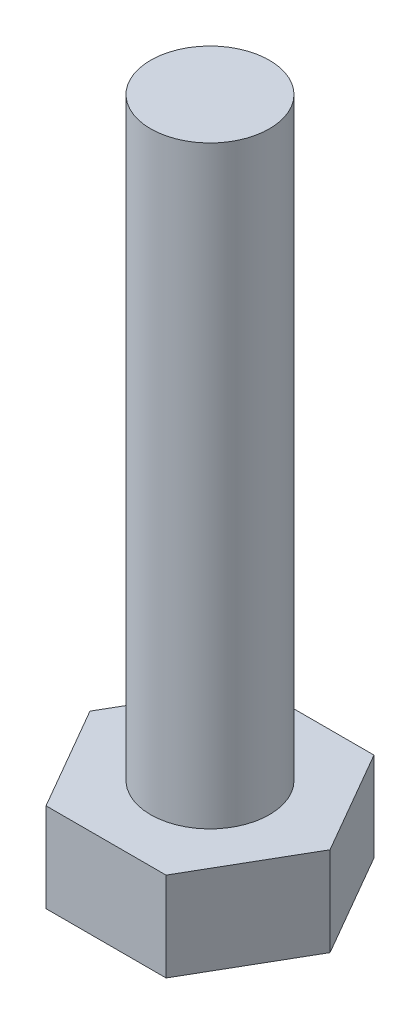
SolidWorks part; units mm, degrees
ref_plane "Front Plane" through (0, 0, 0) normal (0, 0, 1) x (1, 0, 0)
ref_plane "Top Plane" through (0, 0, 0) normal (0, 1, 0) x (1, 0, 0)
ref_plane "Right Plane" through (0, 0, 0) normal (1, 0, 0) x (0, 0, -1)
sketch "Sketch1" plane through (0, 0, 0) normal (0, 1, 0) x (1, 0, 0)
  line L1 (-4.0415, 0) -> (-2.0207, -3.5)
  line L2 (-2.0207, -3.5) -> (2.0207, -3.5)
  line L3 (2.0207, -3.5) -> (4.0415, 0)
  line L4 (4.0415, 0) -> (2.0207, 3.5)
  line L5 (2.0207, 3.5) -> (-2.0207, 3.5)
  line L6 (-2.0207, 3.5) -> (-4.0415, 0)
  circle A0 centre (0, 0) radius 3.5 construction
  dimension "D1" = 7
extrude "Boss-Extrude1" add sketch "Sketch1" along normal blind 3
sketch "Sketch2" plane through (0, 3, 0) normal (0, 1, 0) x (1, 0, 0)
  circle A0 centre (0, 0) radius 2
  dimension "D1" = 4
extrude "Boss-Extrude2" add sketch "Sketch2" along normal blind 20
